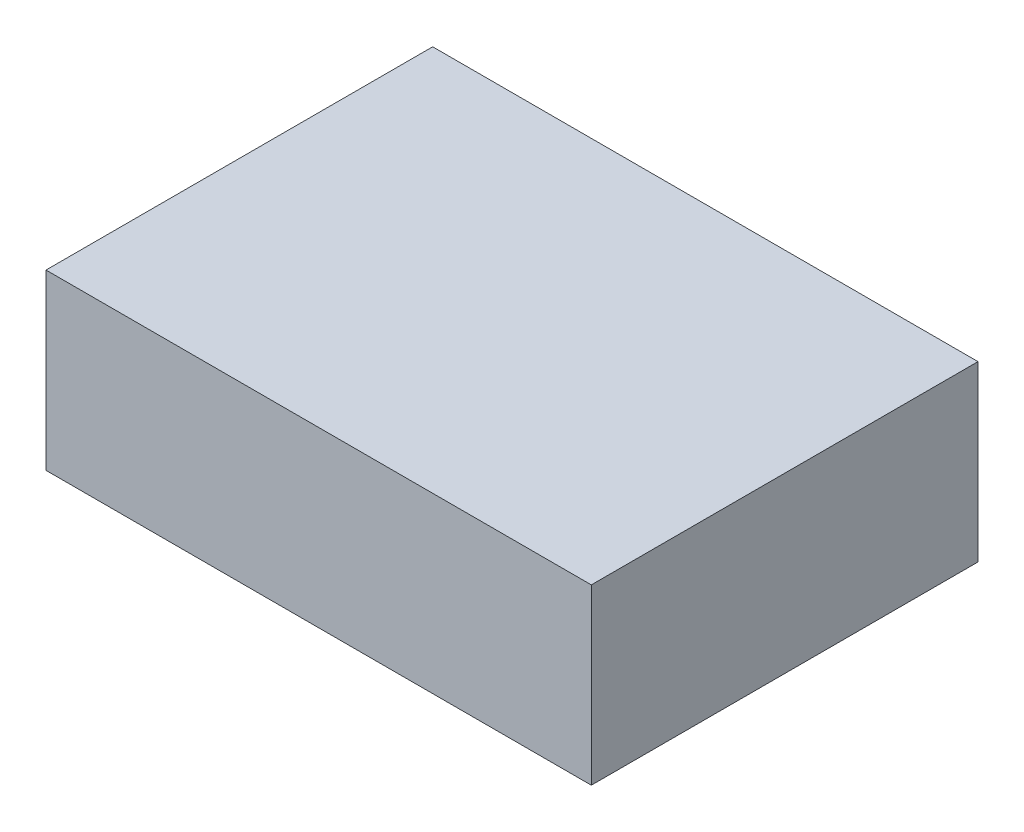
SolidWorks part; units mm, degrees
ref_plane "Front Plane" through (0, 0, 0) normal (0, 0, 1) x (1, 0, 0)
ref_plane "Top Plane" through (0, 0, 0) normal (0, 1, 0) x (1, 0, 0)
ref_plane "Right Plane" through (0, 0, 0) normal (1, 0, 0) x (0, 0, -1)
sketch "Sketch1" plane through (0, 0, 0) normal (0, 1, 0) x (1, 0, 0)
  line L1 (-55, 39) -> (55, 39)
  line L2 (-55, 39) -> (-55, -39)
  line L3 (-55, -39) -> (55, -39)
  line L4 (55, 39) -> (55, -39)
  line L5 (-55, 39) -> (55, -39) construction
  line L6 (-55, -39) -> (55, 39) construction
  point P0 (0, 0)
  dimension "D1" = 110
  dimension "D2" = 78
extrude "Boss-Extrude1" add sketch "Sketch1" along normal blind 35 contours L1 L4 L3 L2
